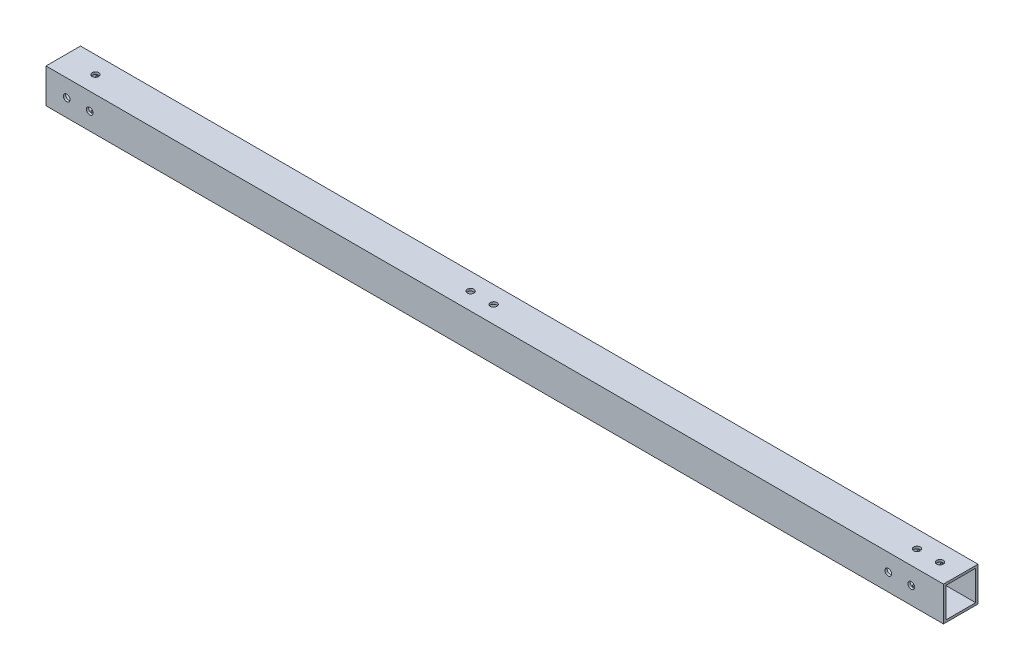
SolidWorks part; units mm, degrees
material "Thornel Mat VMA"
ref_plane "前视基准面" through (0, 0, 0) normal (0, 0, 1) x (1, 0, 0)
ref_plane "上视基准面" through (0, 0, 0) normal (0, 1, 0) x (1, 0, 0)
ref_plane "右视基准面" through (0, 0, 0) normal (1, 0, 0) x (0, 0, -1)
other "Configuration Table"
sketch "草图1" plane through (0, 0, 0) normal (1, 0, 0) x (0, 0, -1)
  line L0 (-6.5, -6.5) -> (-6.5, 6.5)
  line L1 (-7.5, -7.5) -> (7.5, -7.5)
  line L2 (-7.5, -7.5) -> (-7.5, 7.5)
  line L3 (-7.5, 7.5) -> (7.5, 7.5)
  line L4 (7.5, -7.5) -> (7.5, 7.5)
  line L5 (-7.5, -7.5) -> (7.5, 7.5) construction
  line L6 (-7.5, 7.5) -> (7.5, -7.5) construction
  line L7 (-6.5, 6.5) -> (6.5, 6.5)
  line L8 (6.5, -6.5) -> (6.5, 6.5)
  line L9 (-6.5, -6.5) -> (6.5, -6.5)
  point P0 (0, 0)
  dimension "D1" = 15
  dimension "D2" = 15
  dimension "D3" = 1
extrude "凸台-拉伸1" add sketch "草图1" along normal blind 390
sketch "草图2" plane through (0, 0, -7.5) normal (0, 0, -1) x (-1, 0, 0)
  circle A0 centre (-366, 0) radius 1.45 construction
  circle A1 centre (-376, 0) radius 1.45 construction
  circle A2 centre (-19, 0) radius 1.45 construction
  circle A3 centre (-9, 0) radius 1.45 construction
  circle A4 centre (-366, 0) radius 1.45
  circle A5 centre (-376, 0) radius 1.45
  circle A6 centre (-19, 0) radius 1.45
  circle A7 centre (-9, 0) radius 1.45
extrude "切除-拉伸1" cut sketch "草图2" against normal through all
sketch "草图3" plane through (0, 7.5, 0) normal (0, 1, 0) x (1, 0, 0)
  line L0 (-12.09, 0) -> (404.0244, 0) construction
  line L1 (0, 7.5) -> (0, -7.5) construction
  circle A0 centre (371, 0) radius 1.45 construction
  circle A1 centre (381, 0) radius 1.45 construction
  circle A2 centre (14, 0) radius 1.45 construction
  circle A3 centre (371, 0) radius 1.45
  circle A4 centre (381, 0) radius 1.45
  circle A5 centre (14, 0) radius 1.45
  circle A6 centre (177, 0) radius 1.45
  circle A7 centre (187, 0) radius 1.45
  dimension "D1" = 177
  dimension "D3" = 2.9
  dimension "D4" = 2.9
  dimension "D2" = 187
extrude "切除-拉伸2" cut sketch "草图3" against normal through all
